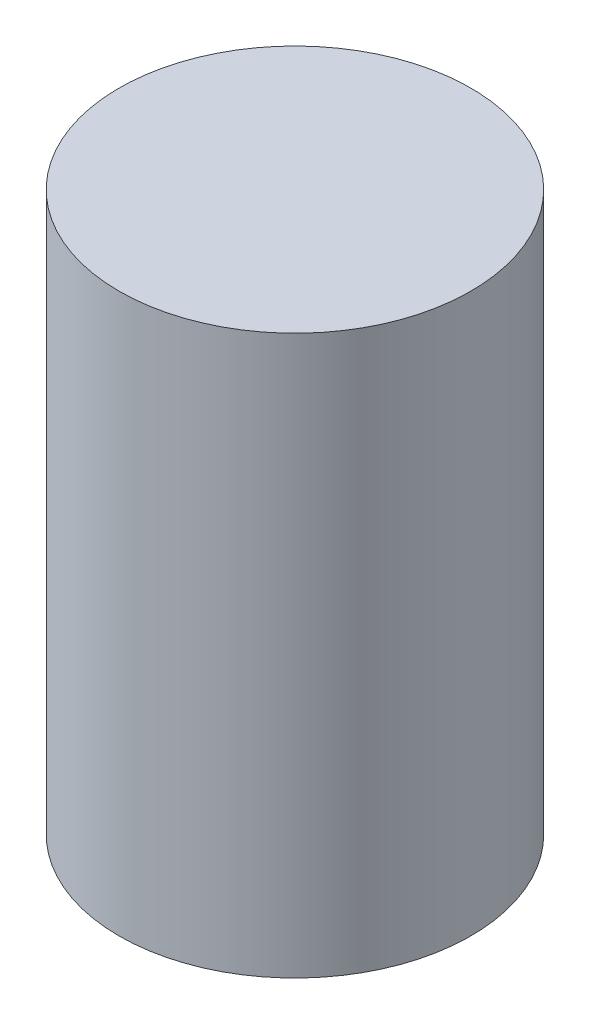
SolidWorks part; units mm, degrees
ref_plane "Front Plane" through (0, 0, 0) normal (0, 0, 1) x (1, 0, 0)
ref_plane "Top Plane" through (0, 0, 0) normal (0, 1, 0) x (1, 0, 0)
ref_plane "Right Plane" through (0, 0, 0) normal (1, 0, 0) x (0, 0, -1)
sketch "Sketch2" plane through (0, 0, 0) normal (0, 1, 0) x (1, 0, 0)
  circle A0 centre (0, 0) radius 16.002
  dimension "D1" = 32.004
extrude "Boss-Extrude1" add sketch "Sketch2" along normal blind 50.8 contours A0
